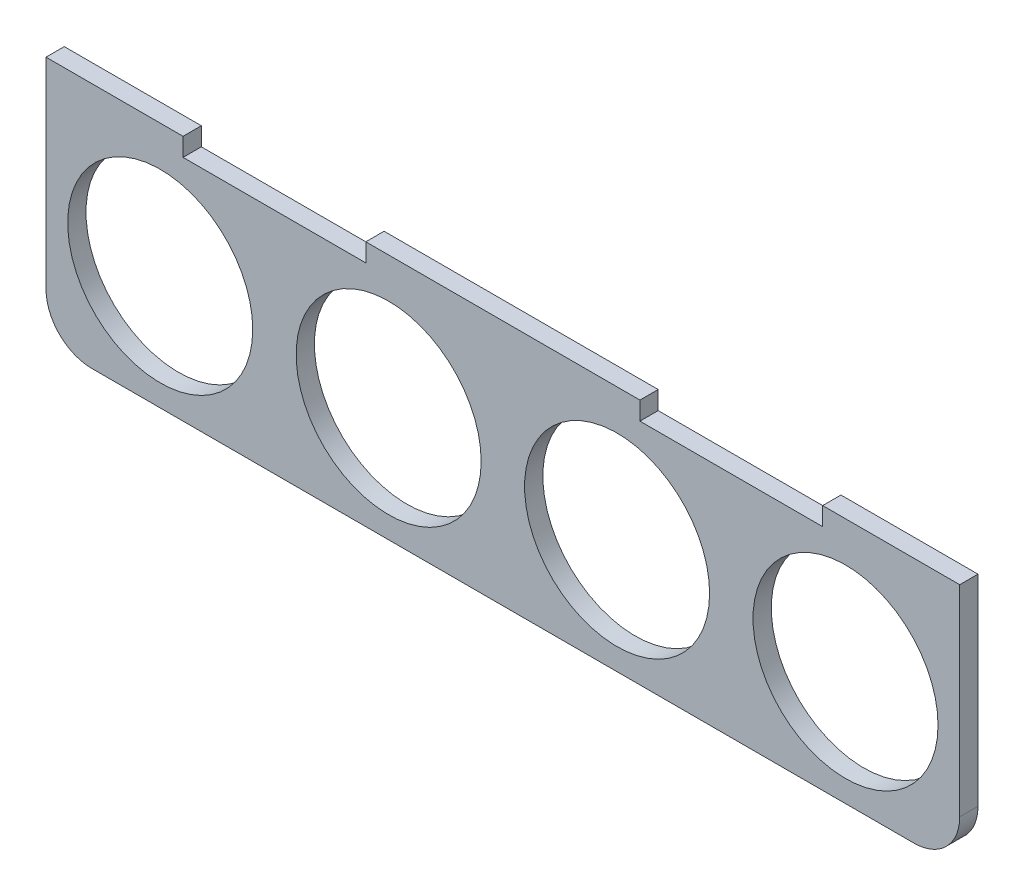
SolidWorks part; units mm, degrees
ref_plane "Front Plane" through (0, 0, 0) normal (0, 0, 1) x (1, 0, 0)
ref_plane "Top Plane" through (0, 0, 0) normal (0, 1, 0) x (1, 0, 0)
ref_plane "Right Plane" through (0, 0, 0) normal (1, 0, 0) x (0, 0, -1)
sketch "Sketch1" plane through (0, 0, 0) normal (0, 0, 1) x (1, 0, 0)
  line L0 (25, 25) -> (75, 25) construction
  line L1 (10, 0) -> (190, 0)
  line L2 (0, 10) -> (0, 50)
  line L3 (30, 50) -> (70, 50)
  line L4 (200, 10) -> (200, 50)
  line L5 (75, 25) -> (125, 25) construction
  line L6 (125, 25) -> (175, 25) construction
  line L7 (130, 50) -> (170, 50)
  line L8 (50, 50) -> (50, 6.6094) construction
  line L9 (0, 50) -> (0, 54)
  line L10 (0, 54) -> (30, 54)
  line L11 (30, 50) -> (30, 54)
  line L13 (200, 50) -> (200, 54)
  line L14 (200, 54) -> (170, 54)
  line L15 (170, 50) -> (170, 54)
  line L17 (70, 50) -> (70, 54)
  line L18 (70, 54) -> (130, 54)
  line L19 (130, 50) -> (130, 54)
  circle A0 centre (25, 25) radius 20.25
  circle A1 centre (75, 25) radius 20.25
  circle A2 centre (125, 25) radius 20.25
  circle A3 centre (175, 25) radius 20.25
  arc A4 (190, 0) -> (200, 10) centre (190, 10) ccw
  arc A5 (10, 0) -> (0, 10) centre (10, 10) cw
  point P17 (0, 0)
  dimension "D3" = 40.5
  dimension "D6" = 10
  dimension "D1" = 200
  dimension "D2" = 50
  dimension "D4" = 25
  dimension "D5" = 25
  dimension "D7" = 4
  dimension "D8" = 4
  dimension "D9" = 4
  dimension "D10" = 40
  dimension "D11" = 40
  dimension "D12" = 30
  dimension "D13" = 50
extrude "Boss-Extrude1" add sketch "Sketch1" along normal blind 4
